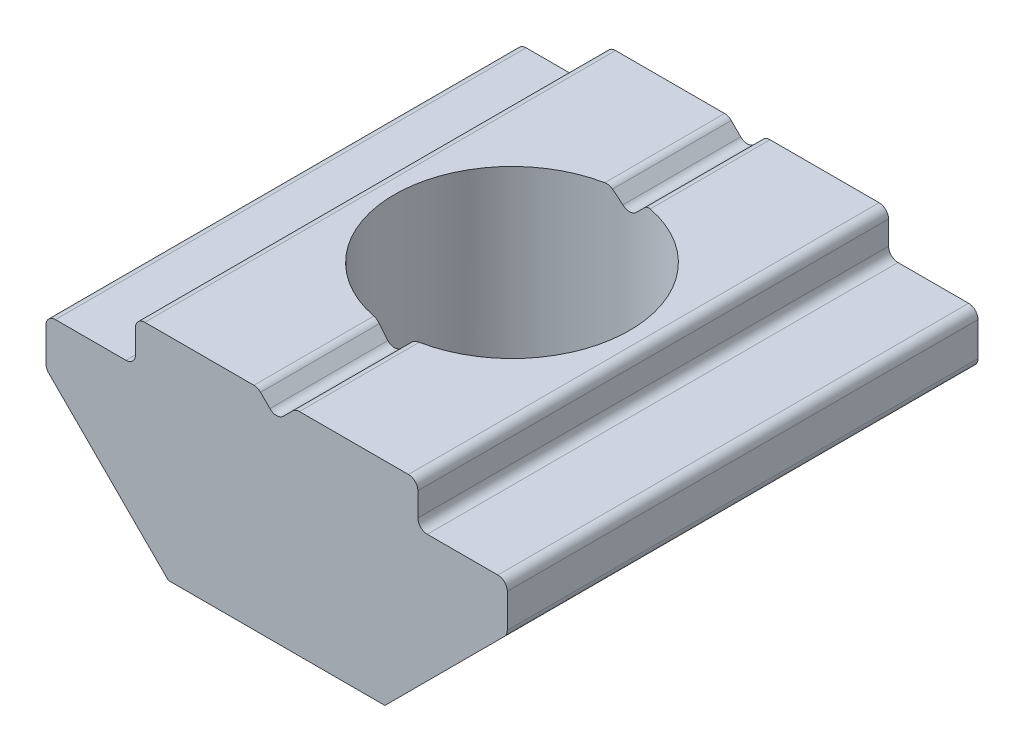
SolidWorks part; units mm, degrees
ref_plane "Front Plane" through (0, 0, 0) normal (0, 0, 1) x (1, 0, 0)
ref_plane "Top Plane" through (0, 0, 0) normal (0, 1, 0) x (1, 0, 0)
ref_plane "Right Plane" through (0, 0, 0) normal (1, 0, 0) x (0, 0, -1)
ref_plane "Plane1" through (0, 0, 5) normal (0, 0, 1) x (1, 0, 0)
sketch "Sketch1" plane through (0, 0, 5) normal (0, 0, 1) x (1, 0, 0)
  line L0 (4.9, -1) -> (4.9, 0.9)
  line L1 (4.9, 0.9) -> (-4.9, 0.9)
  line L2 (-4.9, 0.9) -> (-4.9, -1)
  line L3 (-4.9, -1) -> (-2.3, -3.6)
  line L4 (-2.3, -3.6) -> (2.3, -3.6)
  line L5 (2.3, -3.6) -> (4.9, -1)
extrude "Extrude Body" add sketch "Sketch1" against normal blind 10
sketch "Sketch2" plane through (0, 0, -5) normal (0, 0, -1) x (-1, 0, 0)
  line L0 (4.9, 0.9) -> (3, 0.9)
  line L1 (3, 0.9) -> (3, 0)
  line L2 (3, 0) -> (4.9, 0)
  line L3 (4.9, 0) -> (4.9, 0.9)
extrude "Cut-Extrude1" cut sketch "Sketch2" against normal through all
sketch "Sketch3" plane through (0, 0, -5) normal (0, 0, -1) x (-1, 0, 0)
  line L0 (-4.9, 0) -> (-3, 0)
  line L1 (-3, 0) -> (-3, 0.9)
  line L2 (-3, 0.9) -> (-4.9, 0.9)
  line L3 (-4.9, 0.9) -> (-4.9, 0)
extrude "Cut-Extrude2" cut sketch "Sketch3" against normal through all
sketch "Sketch4" plane through (0, 0, -5) normal (0, 0, -1) x (-1, 0, 0)
  line L0 (0.4, 0.9) -> (-0.4, 0.9)
  line L1 (-0.4, 0.9) -> (0, 0.5)
  line L2 (0, 0.5) -> (0.4, 0.9)
extrude "Cut-Extrude3" cut sketch "Sketch4" against normal through all
hole_wizard "Hole Revolve" positions "Hole Locating Sketch" profile "Hole Cut Out Sketch" hole size "Ø4.2" standard "ANSI Metric" end condition through all
sketch "Hole Locating Sketch" plane through (0, -3.6, 0) normal (0, -1, 0) x (-1, 0, 0)
  point P0 (0, 0)
sketch "Hole Cut Out Sketch" plane through (0, -3.6, 0) normal (1, 0, 0) x (0, 0, -1)
  line L0 (0, 0) -> (0, 4.5)
  line L1 (0, 4.5) -> (2.5, 4.5)
  line L2 (2.5, 4.5) -> (2.5, 0)
  line L5 (2.5, 0) -> (0, 0)
  line L11 (0, -6.35) -> (0, 107.95) construction
  dimension "Thru Hole Dia." = 5
  dimension "Thru Hole Depth" = 4.5
fillet "Edge Fillets" radius 0.2 16 edges at (4.9, 0, 0) (3, 0, 0) (-4.9, -1, 0) (3, 0.9, 0) (-3, 0, 0) (0.4, 0.9, -3.7339) (0, 0.5, 3.75) (-0.4, 0.9, -3.7339) (4.9, -1, 0) (-3, 0.9, 0) (0, 0.5, -3.75) (-0.4, 0.9, 3.7339) (-4.9, 0, 0) (-2.3, -3.6, -2.9899) (0.4, 0.9, 3.7339) (2.3, -3.6, -2.9899)
